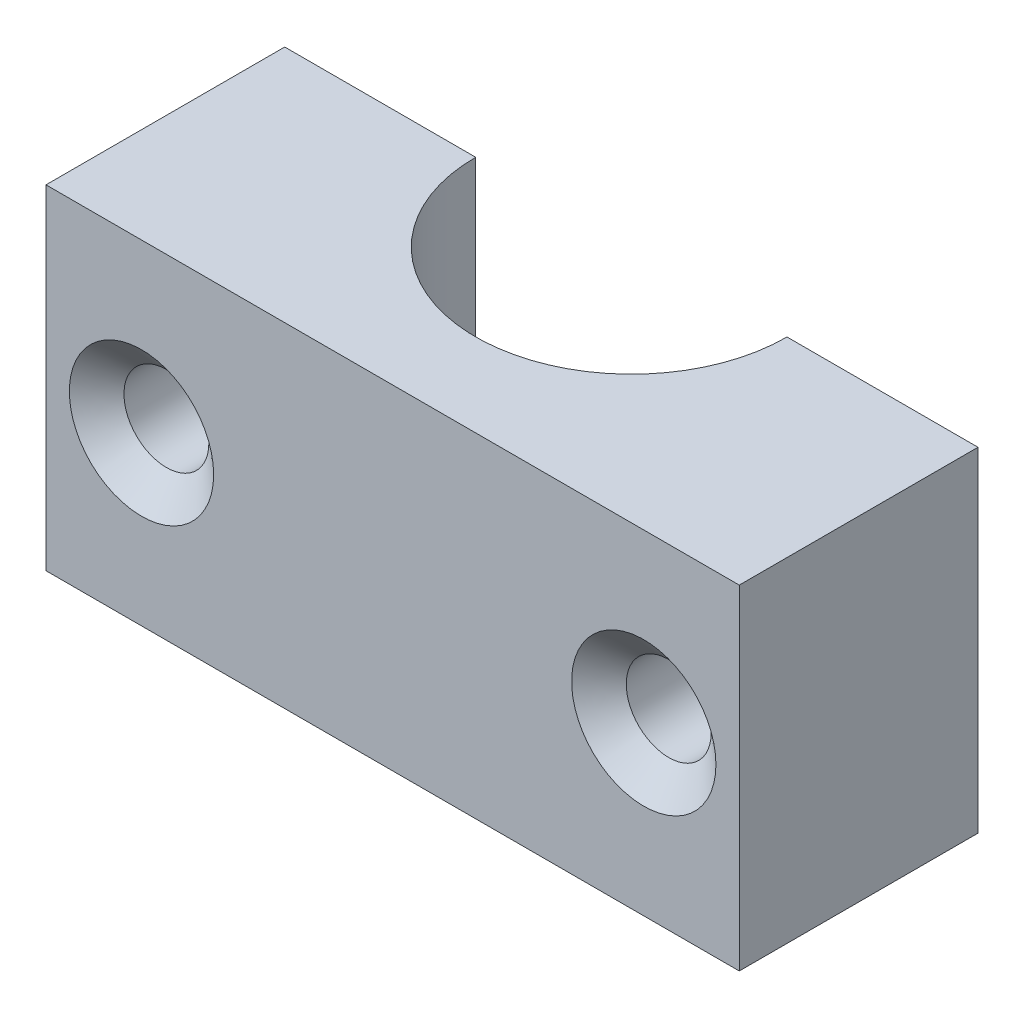
SolidWorks part; units mm, degrees
ref_plane "Front Plane" through (0, 0, 0) normal (0, 0, 1) x (1, 0, 0)
ref_plane "Top Plane" through (0, 0, 0) normal (0, 1, 0) x (1, 0, 0)
ref_plane "Right Plane" through (0, 0, 0) normal (1, 0, 0) x (0, 0, -1)
sketch "Sketch1" plane through (0, 0, 0) normal (0, 1, 0) x (1, 0, 0)
  line L0 (-5.9271, 0) -> (6.3469, 0) construction
  line L1 (-7.26, 0) -> (-3.26, 0)
  line L2 (3.26, 0) -> (7.26, 0)
  line L3 (7.26, 0) -> (7.26, -5)
  line L4 (7.26, -5) -> (-7.26, -5)
  line L5 (-7.26, -5) -> (-7.26, 0)
  circle A0 centre (0, 0) radius 3.26 construction
  arc A1 (-3.26, 0) -> (3.26, 0) centre (0, 0) ccw
  point P5 (0.2099, 0)
  dimension "D1" = 5
  dimension "D2" = 3.26
  dimension "D3" = 4
extrude "Boss-Extrude1" add sketch "Sketch1" along normal blind 7
hole_wizard "CSK for #0 Flat Head Machine Screw (100)1" positions "Sketch3" profile "Sketch4" countersink size "#0" standard "Ansi Inch" end condition through all
sketch "Sketch3" plane through (0, 0, 5) normal (0, 0, 1) x (1, 0, 0)
  line L0 (-7.26, 3.5) -> (7.26, 3.5) construction
  line L1 (-7.26, 7) -> (-7.26, 0) construction
  line L2 (7.26, 7) -> (7.26, 0) construction
  line L4 (0, 7) -> (0, 0) construction
  line L5 (-7.26, 7) -> (7.26, 7) construction
  line L6 (-7.26, 0) -> (7.26, 0) construction
  point P0 (-5.26, 3.5)
  point P22 (5.26, 3.5)
  dimension "D1" = 2
sketch "Sketch4" plane through (-5.26, 3.5, 5) normal (1, 0, 0) x (0, -1, 0)
  line L0 (0, 0) -> (0, 5)
  line L1 (0, 5) -> (0.889, 5)
  line L2 (0.889, 5) -> (0.889, 0.5222)
  line L3 (0.889, 0.5222) -> (1.5113, 0)
  line L5 (1.5113, 0) -> (0, 0)
  line L6 (-0.889, 0.5222) -> (-1.5113, 0) construction
  line L11 (0, -6.35) -> (0, 107.95) construction
  dimension "Thru Hole Dia." = 1.778
  dimension "Thru Hole Depth" = 5
  dimension "Near C'Sink Dia." = 3.0226
  dimension "Near C'Sink Angle" = 100
